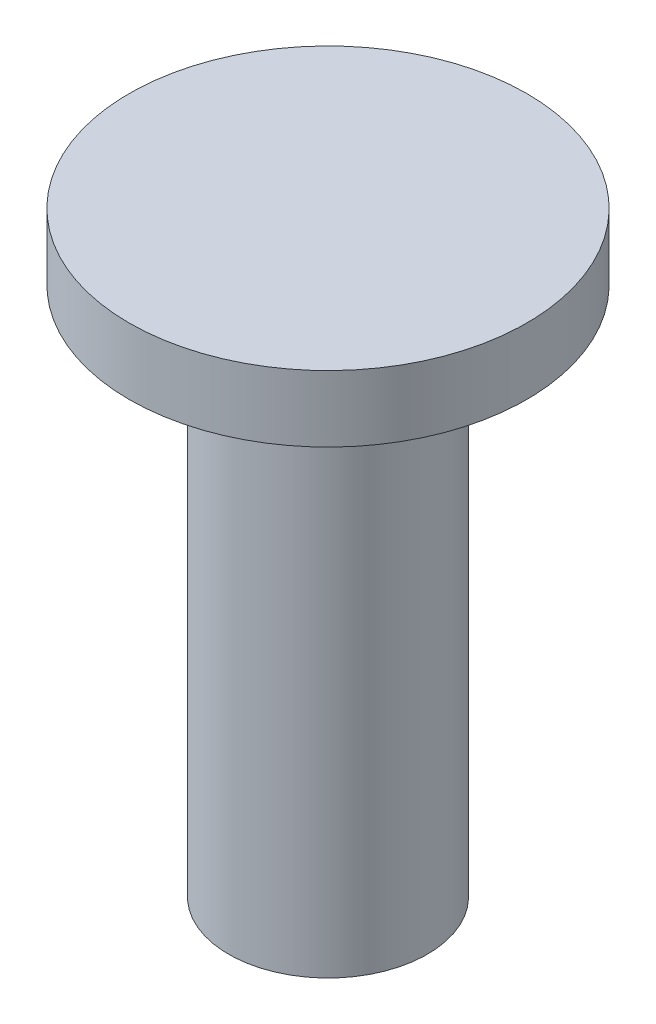
SolidWorks part; units mm, degrees
material "AISI 304"
ref_plane "前视基准面" through (0, 0, 0) normal (0, 0, 1) x (1, 0, 0)
ref_plane "上视基准面" through (0, 0, 0) normal (0, 1, 0) x (1, 0, 0)
ref_plane "右视基准面" through (0, 0, 0) normal (1, 0, 0) x (0, 0, -1)
other "Configuration Table"
sketch "草图1" plane through (0, 0, 0) normal (0, 1, 0) x (1, 0, 0)
  circle A0 centre (0, 0) radius 3
  dimension "D1" = 6
extrude "凸台-拉伸1" add sketch "草图1" along normal blind 1
sketch "草图2" plane through (0, 0, 0) normal (0, -1, 0) x (1, 0, 0)
  circle A0 centre (0, 0) radius 1.5
  dimension "D1" = 3
extrude "凸台-拉伸2" add sketch "草图2" along normal blind 8
